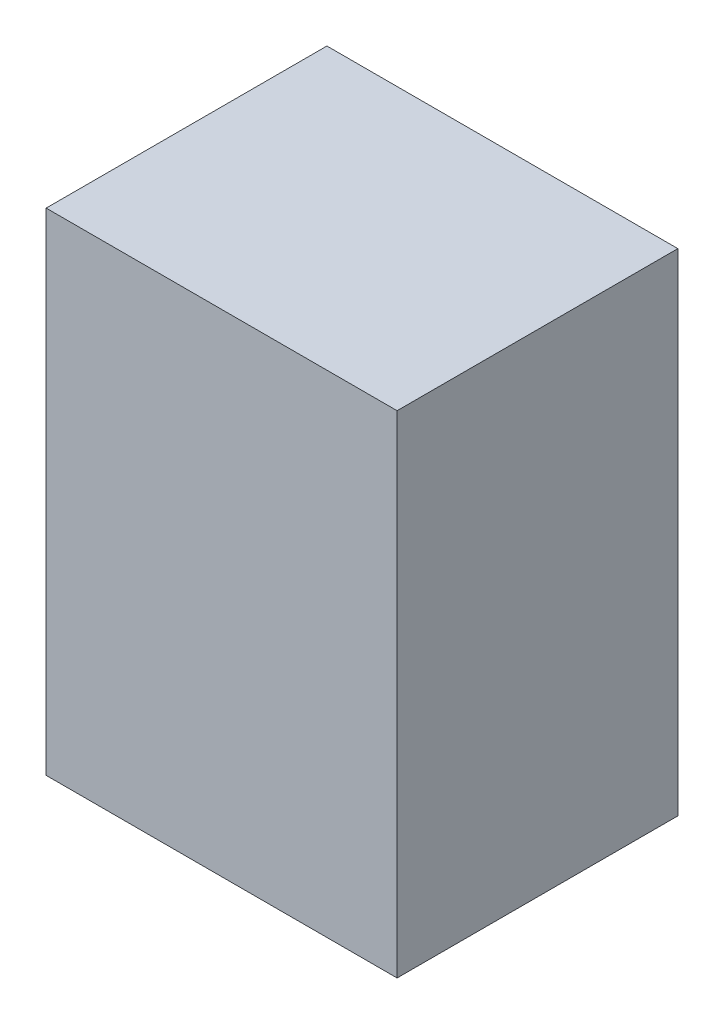
SolidWorks part; units mm, degrees
ref_plane "Front Plane" through (0, 0, 0) normal (0, 0, 1) x (1, 0, 0)
ref_plane "Top Plane" through (0, 0, 0) normal (0, 1, 0) x (1, 0, 0)
ref_plane "Right Plane" through (0, 0, 0) normal (1, 0, 0) x (0, 0, -1)
sketch "Sketch1" plane through (0, 0, 0) normal (0, 1, 0) x (1, 0, 0)
  line L1 (0, 0) -> (254, 0)
  line L2 (0, 0) -> (0, 203.2)
  line L3 (0, 203.2) -> (254, 203.2)
  line L4 (254, 0) -> (254, 203.2)
  dimension "D1" = 254
  dimension "D2" = 203.2
extrude "Boss-Extrude1" add sketch "Sketch1" along normal blind 355.6
